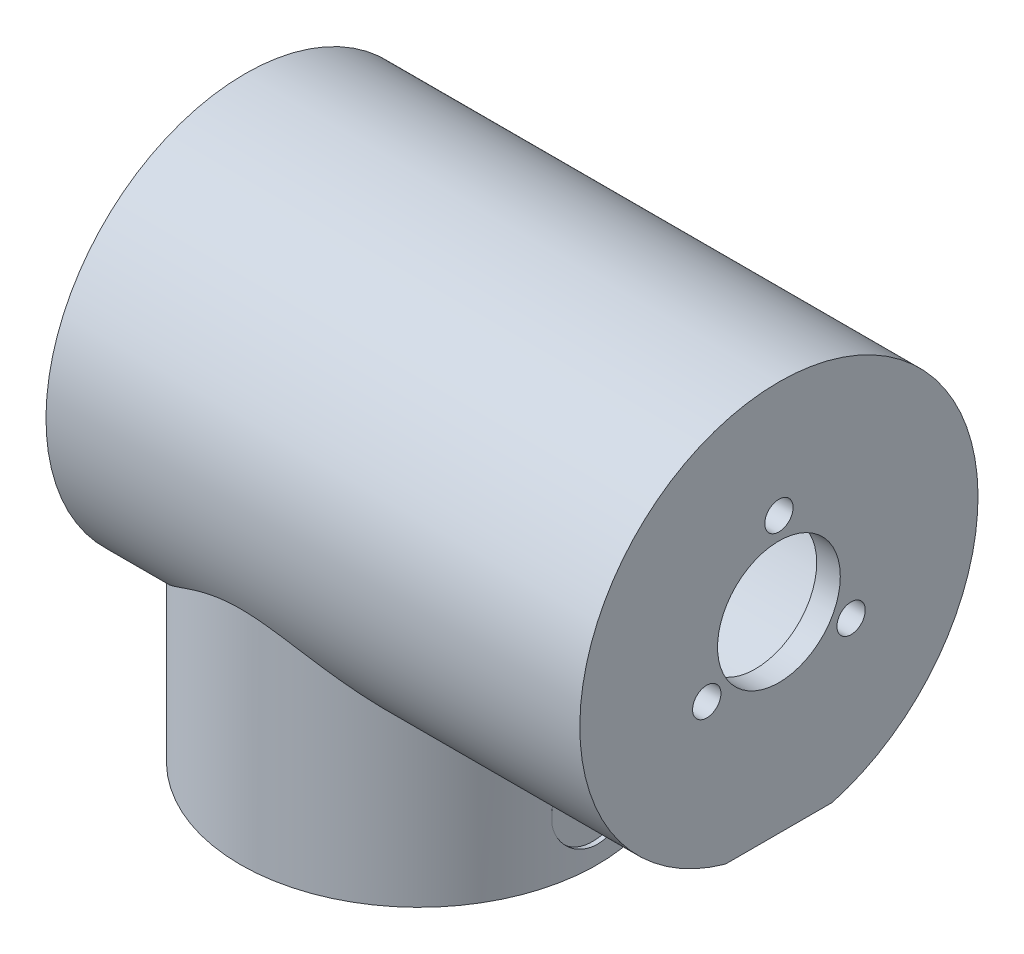
SolidWorks part; units mm, degrees
material "PLA Black"
ref_plane "Front" through (0, 0, 0) normal (0, 0, 1) x (1, 0, 0)
ref_plane "Top" through (0, 0, 0) normal (0, 1, 0) x (1, 0, 0)
ref_plane "Right" through (0, 0, 0) normal (1, 0, 0) x (0, 0, -1)
sketch "Sketch1" plane through (0, 0, 0) normal (0, 1, 0) x (1, 0, 0)
  line L0 (10.125, 0) -> (8.875, 0) construction
  circle A0 centre (0, 0) radius 9.5 construction
  circle A1 centre (0, 0) radius 10.125
  circle A2 centre (0, 0) radius 15.125
  circle A3 centre (0, 0) radius 8.875
  circle A4 centre (0, 0) radius 4.875
  point P10 (9.5, 0)
  dimension "D1" = 19
  dimension "D4" = 4
  dimension "D5" = 1.25
  dimension "D3" = 5
extrude "Boss-Extrude1" add sketch "Sketch1" against normal blind 10 contours A2 A1 | A3 A4
ref_plane "Plane4" through (15.125, 0, 0) normal (1, 0, 0) x (0, 0, -1)
hole_wizard "M3 Clearance Hole1" positions "Sketch29" profile "Sketch28" hole size "M3" standard "DIN" end condition through all
sketch "Sketch29" plane through (15.125, 0, -8.875) normal (1, 0, 0) x (0, 0, -1)
  line L6 (5.466, -5) -> (-26.1974, -5) construction
  line L8 (6.25, 0) -> (-24, 0) construction
  line L9 (-24, -10) -> (6.25, -10) construction
  line L10 (-8.875, 1.8656) -> (-8.875, -11.1628) construction
  point P0 (-8.875, -5)
sketch "Sketch28" plane through (15.125, -5, 0) normal (0, 1, 0) x (0, 0, -1)
  line L0 (0, 0) -> (0, 30.25)
  line L1 (0, 30.25) -> (1.8, 30.25)
  line L2 (1.8, 30.25) -> (1.8, 0)
  line L5 (1.8, 0) -> (0, 0)
  line L11 (0, -6.35) -> (0, 107.95) construction
  dimension "Thru Hole Dia." = 3.6
  dimension "Thru Hole Depth" = 30.25
sketch "Sketch30" plane through (15.125, 0, 0) normal (1, 0, 0) x (0, 0, -1)
  circle A0 centre (0, -5) radius 3.5
  dimension "D1" = 7
extrude "Cut-Extrude4" cut sketch "Sketch30" against normal blind 0.4
mirror "Mirror1" about plane through (0, 0, 0) normal (1, 0, 0) of "Cut-Extrude4"
ref_plane "Plane1" through (28.5, 0, 0) normal (1, 0, 0) x (0, 0, -1)
sketch "Sketch3" plane through (28.5, 0, 0) normal (1, 0, 0) x (0, 0, -1)
  line L0 (0, 33.1806) -> (0, -1.1289) construction
  line L1 (-15.125, -11.9639) -> (-15.125, 18.442) construction
  line L3 (15.125, 0) -> (-15.125, 0) construction
  line L4 (4.518, -0.01) -> (-4.518, -0.01)
  line L5 (-15.125, 0) -> (-15.125, -10) construction
  circle A0 centre (0, 16.24) radius 11.25
  arc A1 (4.518, -0.01) -> (-4.518, -0.01) centre (0, 16.24) ccw
  point P13 (0, 16.24)
  point P16 (0, 4.99)
  dimension "D1" = 22.5
  dimension "D2" = 5
  dimension "D3" = 0.01
extrude "Boss-Extrude3" add sketch "Sketch3" against normal up to surface (43.225 mm away)
sketch "Sketch2" plane through (0, 0, 0) normal (0, 1, 0) x (1, 0, 0)
  line L0 (14.4232, -4.5538) -> (-14.4232, -4.5538)
  line L1 (-14.4232, -4.5538) -> (-9.0432, -4.5538) construction
  line L2 (28.729, 0) -> (-18.1199, 0) construction
  line L3 (14.4232, 4.5538) -> (-14.4232, 4.5538)
  arc A1 (14.4232, -4.5538) -> (-14.4232, -4.5538) centre (0, 0) cw
  arc A4 (-14.4232, -4.5538) -> (14.4232, -4.5538) centre (0, 0) ccw construction
  arc A5 (14.4232, 4.5538) -> (-14.4232, 4.5538) centre (0, 0) ccw
extrude "Boss-Extrude2" add sketch "Sketch2" along normal up to surface contours A1 L3 | L0 A5 up to face at (0.7653, 1.8342, 0)
sketch "Sketch31" plane through (28.5, 0, 0) normal (1, 0, 0) x (0, 0, -1)
  line L0 (-4.518, -0.01) -> (4.518, -0.01) construction
  line L1 (-4.518, -0.01) -> (4.518, -0.01)
  arc A0 (4.518, -0.01) -> (-4.518, -0.01) centre (0, 16.24) ccw construction
  arc A1 (4.518, -0.01) -> (-4.518, -0.01) centre (0, 16.24) ccw
  circle A2 centre (0, 16.24) radius 5.2
  dimension "D1" = 10.4
extrude "Boss-Extrude4" add sketch "Sketch31" along normal blind 2
hole_wizard "M2 Clearance Hole1" positions "Sketch13" profile "Sketch12" hole size "M2" standard "DIN" end condition through all
sketch "Sketch13" plane through (30.5, 0, 0) normal (-1, 0, 0) x (0, 0, 1)
  circle A1 centre (0, 16.24) radius 5.2 construction
  point P0 (0, 23.3)
  point P11 (6.1141, 12.71)
  point P12 (-6.1141, 12.71)
  point P13 (0, 16.24)
  dimension "D1" = 7.06
  dimension "D2" = 3
sketch "Sketch12" plane through (30.5, 23.3, 0) normal (0, 1, 0) x (0, 0, -1)
  line L0 (0, 0) -> (0, 45.625)
  line L1 (0, 45.625) -> (1.2, 45.625)
  line L2 (1.2, 45.625) -> (1.2, 0)
  line L5 (1.2, 0) -> (0, 0)
  line L11 (0, -6.35) -> (0, 107.95) construction
  dimension "Thru Hole Dia." = 2.4
  dimension "Thru Hole Depth" = 45.625
